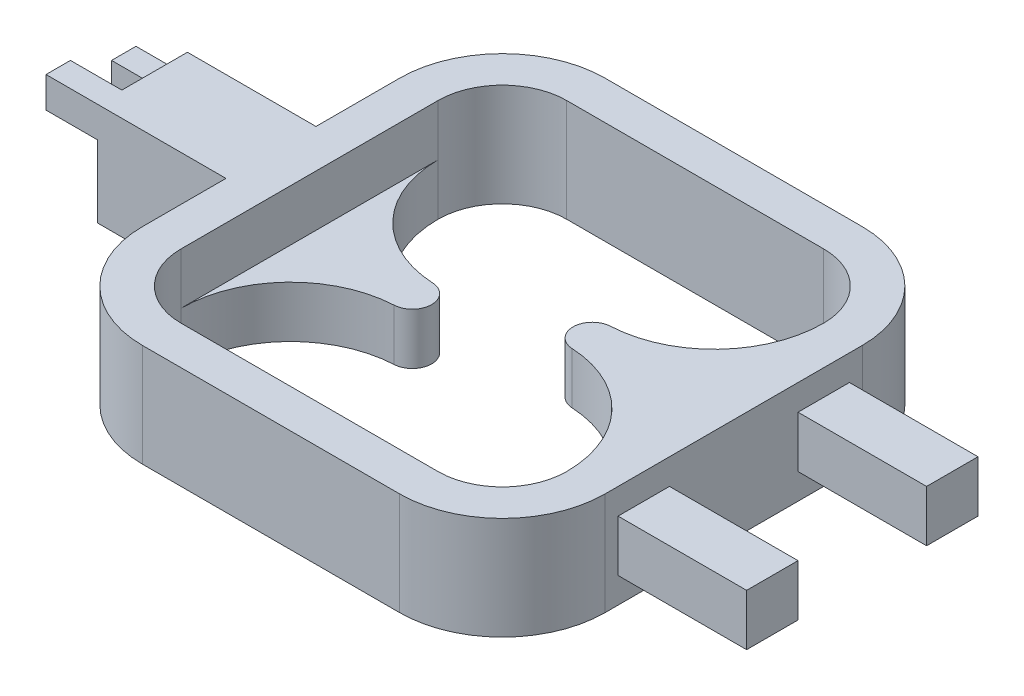
SolidWorks part; units mm, degrees
ref_plane "Front Plane" through (0, 0, 0) normal (0, 0, 1) x (1, 0, 0)
ref_plane "Top Plane" through (0, 0, 0) normal (0, 1, 0) x (1, 0, 0)
ref_plane "Right Plane" through (0, 0, 0) normal (1, 0, 0) x (0, 0, -1)
sketch "Sketch1" plane through (0, 0, 0) normal (0, 1, 0) x (1, 0, 0)
  line L0 (-18, -10) -> (-18, -3.5)
  line L1 (-10, -15) -> (10, -15)
  line L3 (-10, 15) -> (10, 15)
  line L5 (0, 15) -> (0, -15) construction
  line L6 (-15, 0) -> (15, 0) construction
  line L7 (-10, 18) -> (10, 18)
  line L8 (18, -10) -> (18, -9)
  line L9 (-10, -18) -> (10, -18)
  line L10 (-15, -10) -> (-15, 10) construction
  line L11 (15, -10) -> (15, 10) construction
  line L12 (18, 9) -> (18, 10)
  line L13 (18, 9) -> (28, 9)
  line L15 (18, 5) -> (28, 5)
  line L16 (28, 9) -> (28, 5)
  line L17 (23, 5) -> (23, 9) construction
  line L18 (18, 7) -> (28, 7) construction
  line L19 (18, -10) -> (18, 10) construction
  line L20 (23, -5) -> (23, -9) construction
  line L21 (18, -7) -> (28, -7) construction
  line L22 (18, -5) -> (28, -5)
  line L23 (28, -9) -> (28, -5)
  line L24 (18, -9) -> (28, -9)
  line L25 (18, -5) -> (18, 5)
  line L26 (-18, 3.5) -> (-18, 10)
  line L27 (-18, 3.5) -> (-28, 3.5)
  line L29 (-18, -3.5) -> (-28, -3.5)
  line L30 (-28, 3.5) -> (-28, -3.5)
  line L31 (-23, -3.5) -> (-23, 3.5) construction
  line L32 (-18, 0) -> (-28, 0) construction
  line L33 (-18, -10) -> (-18, 10) construction
  arc A0 (-10, -15) -> (-15, -10) centre (-10, -10) cw
  arc A1 (10, -15) -> (15, -10) centre (10, -10) ccw
  arc A2 (10, 15) -> (15, 10) centre (10, 10) cw
  arc A3 (-15, 10) -> (-10, 15) centre (-10, 10) cw
  arc A4 (-18, 10) -> (-10, 18) centre (-10, 10) cw
  arc A5 (10, 18) -> (18, 10) centre (10, 10) cw
  arc A6 (10, -18) -> (18, -10) centre (10, -10) ccw
  arc A7 (-10, -18) -> (-18, -10) centre (-10, -10) cw
  arc A8 (-6.9231, -1.498) -> (-6.9231, 1.498) centre (-7, 0) ccw
  arc A9 (-15, 10) -> (-6.9231, 1.498) centre (-6.4868, 10) ccw
  arc A10 (-15, -10) -> (-6.9231, -1.498) centre (-6.4868, -10) cw
  arc A11 (15, -10) -> (6.9231, -1.498) centre (6.4868, -10) ccw
  arc A12 (6.9231, -1.498) -> (6.9231, 1.498) centre (7, 0) cw
  arc A13 (15, 10) -> (6.9231, 1.498) centre (6.4868, 10) cw
  point P0 (0, 0)
  point P6 (-15, -15)
  point P14 (-15, 15)
  point P27 (-5.5, 0)
  point P206 (23, 7)
  point P292 (-23, 0)
  dimension "D2" = 5
  dimension "D6" = 3
  dimension "D7" = 8.5132
  dimension "D8" = 8.5132
  dimension "D1" = 30
  dimension "D4" = 36
  dimension "D5" = 20
  dimension "D9" = 30
  dimension "D10" = 3
  dimension "D11" = 9.5
  dimension "D12" = 20
  dimension "D13" = 20
  dimension "D14" = 0.0769
  dimension "D15" = 3
  dimension "D16" = 4
  dimension "D17" = 10
  dimension "D18" = 5
  dimension "D19" = 7
  dimension "D20" = 10
  dimension "D3" = 3
extrude "Boss-Extrude1" add sketch "Sketch1" along normal blind 8
sketch "Sketch2" plane through (-28, 0, 0) normal (-1, 0, 0) x (0, 0, 1)
  line L0 (-3.5, 8) -> (3.5, 8) construction
  line L5 (-3.5, 8) -> (-3.5, 0) construction
  line L6 (-3.5, 8) -> (3.5, 8) construction
  line L7 (-3.5, 8) -> (-3.5, 4) construction
  line L9 (-3.5, 4) -> (3.5, 4) construction
  line L13 (3.5, 8) -> (3.5, 4) construction
  line L14 (0, 4) -> (0, 8) construction
  line L15 (-3.5, 6) -> (3.5, 6) construction
  line L16 (3.5, 8) -> (3.5, 0) construction
  line L18 (1.6, 8) -> (3.5, 8)
  line L19 (1.6, 8) -> (1.6, 5.6)
  line L20 (1.6, 5.6) -> (3.5, 5.6)
  line L21 (3.5, 8) -> (3.5, 5.6)
  line L22 (2.55, 5.6) -> (2.55, 8) construction
  line L23 (1.6, 6.8) -> (3.5, 6.8) construction
  line L24 (-3.5, 4) -> (-1.6, 4)
  line L25 (-3.5, 4) -> (-3.5, 6.4)
  line L26 (-3.5, 6.4) -> (-1.6, 6.4)
  line L27 (-1.6, 4) -> (-1.6, 6.4)
  line L28 (-2.55, 6.4) -> (-2.55, 4) construction
  line L29 (-3.5, 5.2) -> (-1.6, 5.2) construction
  point P97 (2.55, 6.8)
  point P111 (0, 6)
  point P192 (-2.55, 5.2)
  dimension "D1" = 4
  dimension "D2" = 1.9
  dimension "D3" = 2.4
  dimension "D4" = 1.9
  dimension "D5" = 2.4
extrude "Boss-Extrude2" add sketch "Sketch2" along normal blind 4
sketch "Sketch3" plane through (28, 0, 0) normal (1, 0, 0) x (0, 0, -1)
  line L0 (-9, 4) -> (9, 4) construction
  line L1 (-9, 8) -> (-9, 0) construction
  line L2 (9, 8) -> (9, 0) construction
  line L3 (9, 2) -> (-9, 2) construction
  line L4 (9, 2) -> (9, 6) construction
  line L5 (-9, 2) -> (-9, 6) construction
  line L6 (9, 6) -> (-9, 6) construction
  line L7 (-9, 4) -> (9, 4) construction
  line L8 (0, 2) -> (0, 6) construction
  line L9 (-9, 2) -> (9, 2)
  line L10 (-9, 8) -> (9, 8)
  line L11 (-9, 8) -> (-9, 6)
  line L12 (-9, 6) -> (9, 6)
  line L13 (9, 8) -> (9, 6)
  line L14 (0, 6) -> (0, 8) construction
  line L15 (-9, 7) -> (9, 7) construction
  line L16 (9, 0) -> (9, 2)
  line L17 (-9, 0) -> (9, 0)
  line L18 (-9, 0) -> (-9, 2)
  point P7 (0, 4)
  point P204 (0, 7)
  dimension "D1" = 4
extrude "Cut-Extrude1" cut sketch "Sketch3" against normal up to surface (10 mm away) up to face at (18, 4, 0)
sketch "Sketch4" plane through (0, 0, 0) normal (0, -1, 0) x (1, 0, 0)
  line L1 (15, -10) -> (5.5, -10)
  line L2 (15, -10) -> (15, 10)
  line L3 (15, 10) -> (5.5, 10)
  line L4 (5.5, -10) -> (5.5, 10)
  line L5 (10.25, 10) -> (10.25, -10) construction
  line L6 (15, 0) -> (5.5, 0) construction
  arc A0 (6.9231, 1.498) -> (6.9231, -1.498) centre (7, 0) ccw construction
  point P384 (10.25, 0)
extrude "Cut-Extrude2" cut sketch "Sketch4" against normal blind 4
sketch "Sketch5" plane through (0, 8, 0) normal (0, 1, 0) x (1, 0, 0)
  line L1 (-15, -10) -> (-5.5, -10)
  line L2 (-15, -10) -> (-15, 10)
  line L3 (-15, 10) -> (-5.5, 10)
  line L4 (-5.5, -10) -> (-5.5, 10)
  line L5 (-10.25, 10) -> (-10.25, -10) construction
  line L6 (-15, 0) -> (-5.5, 0) construction
  arc A0 (-6.9231, -1.498) -> (-6.9231, 1.498) centre (-7, 0) ccw construction
  point P348 (-10.25, 0)
extrude "Cut-Extrude3" cut sketch "Sketch5" against normal blind 4
equation "\"D8@Sketch1\"=\"D7@Sketch1\""
equation "\"D4@Sketch2\"=\"D2@Sketch2\""
equation "\"D5@Sketch2\"=\"D3@Sketch2\""
